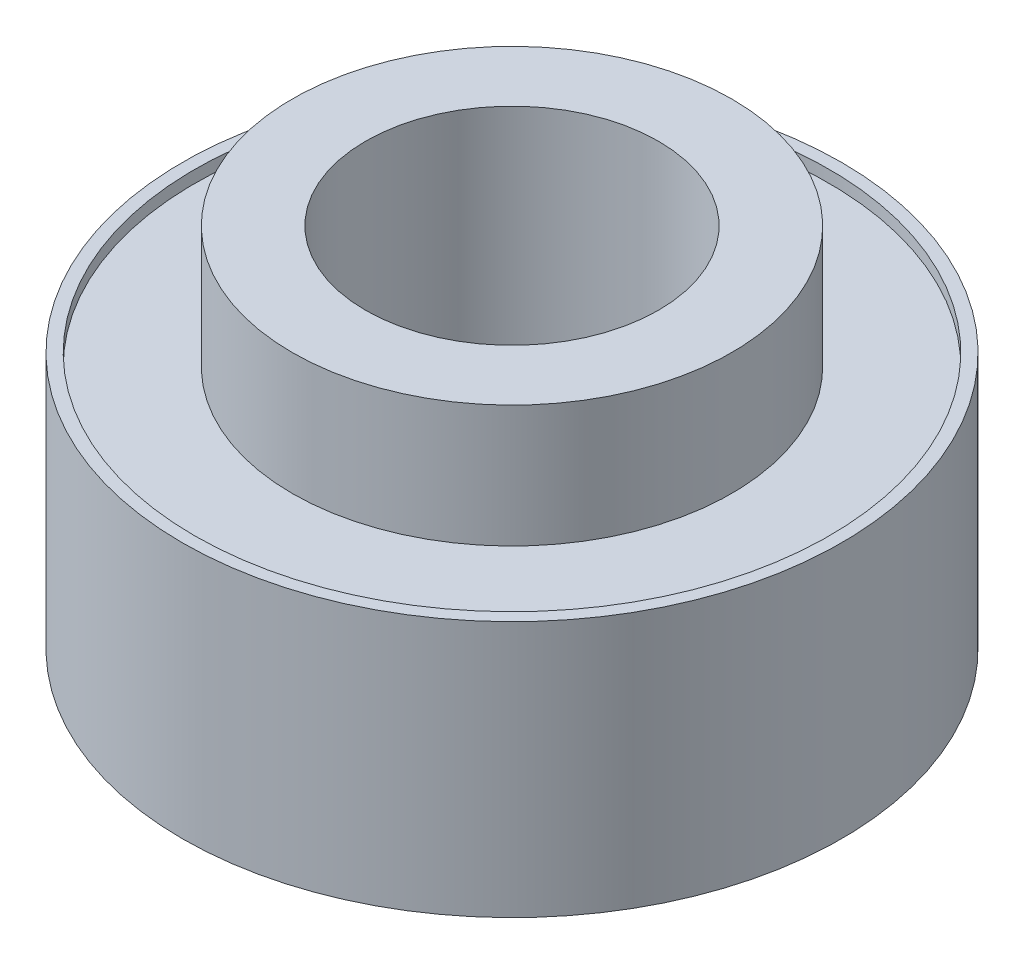
SolidWorks part; units mm, degrees
material "Простая углеродистая сталь"
ref_plane "Спереди" through (0, 0, 0) normal (0, 0, 1) x (1, 0, 0)
ref_plane "Сверху" through (0, 0, 0) normal (0, 1, 0) x (1, 0, 0)
ref_plane "Справа" through (0, 0, 0) normal (1, 0, 0) x (0, 0, -1)
sketch "Эскиз1" plane through (0, 0, 0) normal (0, 1, 0) x (1, 0, 0)
  circle A0 centre (0, 0) radius 13.5
  dimension "D1" = 27
extrude "Бобышка-Вытянуть1" add sketch "Эскиз1" along normal blind 10.5
sketch "Эскиз2" plane through (0, 10.5, 0) normal (0, 1, 0) x (1, 0, 0)
  circle A0 centre (0, 0) radius 13
  circle A1 centre (0, 0) radius 13.5 construction
  dimension "D1" = 0.5
extrude "Вырез-Вытянуть1" cut sketch "Эскиз2" against normal blind 0.5
sketch "Эскиз3" plane through (0, 0, 0) normal (0, -1, 0) x (1, 0, 0)
  circle A0 centre (0, 0) radius 13
  circle A1 centre (0, 0) radius 13.5 construction
  dimension "D1" = 0.5
extrude "Вырез-Вытянуть2" cut sketch "Эскиз3" against normal blind 0.5
sketch "Эскиз4" plane through (0, 10, 0) normal (0, 1, 0) x (1, 0, 0)
  circle A0 centre (0, 0) radius 6
  dimension "D1" = 12
extrude "Вырез-Вытянуть3" cut sketch "Эскиз4" against normal through all
sketch "Эскиз5" plane through (0, 10, 0) normal (0, 1, 0) x (1, 0, 0)
  circle A0 centre (0, 0) radius 9
  circle A1 centre (0, 0) radius 6 construction
  circle A2 centre (0, 0) radius 6
  dimension "D1" = 3
extrude "Бобышка-Вытянуть2" add sketch "Эскиз5" along normal blind 5
sketch "Эскиз6" plane through (0, 0.5, 0) normal (0, -1, 0) x (1, 0, 0)
  circle A0 centre (0, 0) radius 6 construction
  circle A1 centre (0, 0) radius 9
  circle A2 centre (0, 0) radius 9
  circle A3 centre (0, 0) radius 6
  dimension "D1" = 0
extrude "Бобышка-Вытянуть3" add sketch "Эскиз6" along normal blind 1.5
